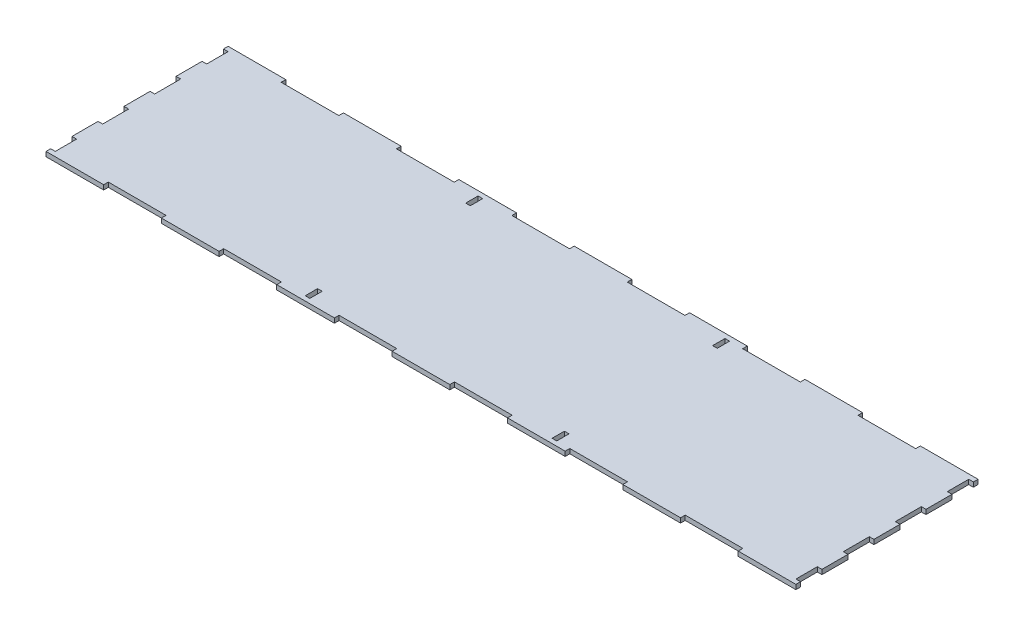
SolidWorks part; units mm, degrees
ref_plane "Front Plane" through (0, 0, 0) normal (0, 0, 1) x (1, 0, 0)
ref_plane "Top Plane" through (0, 0, 0) normal (0, 1, 0) x (1, 0, 0)
ref_plane "Right Plane" through (0, 0, 0) normal (1, 0, 0) x (0, 0, -1)
sketch "Sketch1" plane through (0, 0, 0) normal (0, 1, 0) x (1, 0, 0)
  line L0 (0, 88.9) -> (0, -88.9) construction
  line L1 (-381, 88.9) -> (381, 88.9)
  line L2 (-381, 88.9) -> (-381, -88.9)
  line L3 (-381, -88.9) -> (381, -88.9)
  line L4 (381, 88.9) -> (381, -88.9)
  line L5 (-381, 40.1411) -> (-381, 66.9018)
  line L6 (-381, 66.9018) -> (-385.7625, 66.9018)
  line L7 (-381, 66.9018) -> (-381, 93.6625)
  line L8 (-381, 93.6625) -> (-385.7625, 93.6625)
  line L9 (-385.7625, 66.9018) -> (-385.7625, 93.6625)
  line L14 (-326.4144, -88.9) -> (-385.7625, -88.9)
  line L15 (-326.4144, -88.9) -> (-326.4144, -93.6625)
  line L16 (-326.4144, -93.6625) -> (-385.7625, -93.6625)
  line L17 (-385.7625, -88.9) -> (-385.7625, -93.6625)
  line L18 (381, 66.9018) -> (385.7625, 66.9018)
  line L19 (381, 66.9018) -> (381, 93.6625)
  line L20 (381, 93.6625) -> (385.7625, 93.6625)
  line L21 (385.7625, 66.9018) -> (385.7625, 93.6625)
  line L22 (-326.4144, 88.9) -> (-385.7625, 88.9)
  line L23 (-326.4144, 88.9) -> (-326.4144, 93.6625)
  line L24 (-326.4144, 93.6625) -> (-385.7625, 93.6625)
  line L25 (-385.7625, 88.9) -> (-385.7625, 93.6625)
  line L26 (-381, 40.1411) -> (-385.7625, 40.1411)
  line L27 (-385.7625, 40.1411) -> (-385.7625, 66.9018)
  line L28 (-381, 66.9018) -> (-385.7625, 66.9018)
  line L29 (381, 40.1411) -> (381, 66.9018)
  line L30 (381, 40.1411) -> (385.7625, 40.1411)
  line L31 (385.7625, 40.1411) -> (385.7625, 66.9018)
  line L32 (381, 66.9018) -> (385.7625, 66.9018)
  line L33 (-381, 13.3804) -> (-381, 40.1411)
  line L34 (-381, 13.3804) -> (-385.7625, 13.3804)
  line L35 (-385.7625, 13.3804) -> (-385.7625, 40.1411)
  line L36 (-381, 40.1411) -> (-385.7625, 40.1411)
  line L37 (381, 13.3804) -> (381, 40.1411)
  line L38 (381, 13.3804) -> (385.7625, 13.3804)
  line L39 (385.7625, 13.3804) -> (385.7625, 40.1411)
  line L40 (381, 40.1411) -> (385.7625, 40.1411)
  line L41 (-381, -13.3804) -> (-381, 13.3804)
  line L42 (-381, -13.3804) -> (-385.7625, -13.3804)
  line L43 (-385.7625, -13.3804) -> (-385.7625, 13.3804)
  line L44 (-381, 13.3804) -> (-385.7625, 13.3804)
  line L45 (381, -13.3804) -> (381, 13.3804)
  line L46 (381, -13.3804) -> (385.7625, -13.3804)
  line L47 (385.7625, -13.3804) -> (385.7625, 13.3804)
  line L48 (381, 13.3804) -> (385.7625, 13.3804)
  line L49 (-381, -40.1411) -> (-381, -13.3804)
  line L50 (-381, -40.1411) -> (-385.7625, -40.1411)
  line L51 (-385.7625, -40.1411) -> (-385.7625, -13.3804)
  line L52 (-381, -13.3804) -> (-385.7625, -13.3804)
  line L53 (381, -40.1411) -> (381, -13.3804)
  line L54 (381, -40.1411) -> (385.7625, -40.1411)
  line L55 (385.7625, -40.1411) -> (385.7625, -13.3804)
  line L56 (381, -13.3804) -> (385.7625, -13.3804)
  line L57 (-381, -66.9018) -> (-381, -40.1411)
  line L58 (-381, -66.9018) -> (-385.7625, -66.9018)
  line L59 (-385.7625, -66.9018) -> (-385.7625, -40.1411)
  line L60 (-381, -40.1411) -> (-385.7625, -40.1411)
  line L61 (381, -66.9018) -> (381, -40.1411)
  line L62 (381, -66.9018) -> (385.7625, -66.9018)
  line L63 (385.7625, -66.9018) -> (385.7625, -40.1411)
  line L64 (381, -40.1411) -> (385.7625, -40.1411)
  line L65 (-381, -93.6625) -> (-381, -66.9018)
  line L66 (-381, -93.6625) -> (-385.7625, -93.6625)
  line L67 (-385.7625, -93.6625) -> (-385.7625, -66.9018)
  line L68 (-381, -66.9018) -> (-385.7625, -66.9018)
  line L69 (381, -93.6625) -> (381, -66.9018)
  line L70 (381, -93.6625) -> (385.7625, -93.6625)
  line L71 (385.7625, -93.6625) -> (385.7625, -66.9018)
  line L72 (381, -66.9018) -> (385.7625, -66.9018)
  line L73 (-267.0663, -88.9) -> (-267.0663, -93.6625)
  line L74 (-267.0663, -88.9) -> (-326.4144, -88.9)
  line L75 (-326.4144, -88.9) -> (-326.4144, -93.6625)
  line L76 (-267.0663, -93.6625) -> (-326.4144, -93.6625)
  line L77 (-267.0663, 88.9) -> (-267.0663, 93.6625)
  line L78 (-267.0663, 88.9) -> (-326.4144, 88.9)
  line L79 (-326.4144, 88.9) -> (-326.4144, 93.6625)
  line L80 (-267.0663, 93.6625) -> (-326.4144, 93.6625)
  line L81 (-207.7183, -88.9) -> (-207.7183, -93.6625)
  line L82 (-207.7183, -88.9) -> (-267.0663, -88.9)
  line L83 (-267.0663, -88.9) -> (-267.0663, -93.6625)
  line L84 (-207.7183, -93.6625) -> (-267.0663, -93.6625)
  line L85 (-207.7183, 88.9) -> (-207.7183, 93.6625)
  line L86 (-207.7183, 88.9) -> (-267.0663, 88.9)
  line L87 (-267.0663, 88.9) -> (-267.0663, 93.6625)
  line L88 (-207.7183, 93.6625) -> (-267.0663, 93.6625)
  line L89 (-148.3702, -88.9) -> (-148.3702, -93.6625)
  line L90 (-148.3702, -88.9) -> (-207.7183, -88.9)
  line L91 (-207.7183, -88.9) -> (-207.7183, -93.6625)
  line L92 (-148.3702, -93.6625) -> (-207.7183, -93.6625)
  line L93 (-148.3702, 88.9) -> (-148.3702, 93.6625)
  line L94 (-148.3702, 88.9) -> (-207.7183, 88.9)
  line L95 (-207.7183, 88.9) -> (-207.7183, 93.6625)
  line L96 (-148.3702, 93.6625) -> (-207.7183, 93.6625)
  line L97 (-89.0221, -88.9) -> (-89.0221, -93.6625)
  line L98 (-89.0221, -88.9) -> (-148.3702, -88.9)
  line L99 (-148.3702, -88.9) -> (-148.3702, -93.6625)
  line L100 (-89.0221, -93.6625) -> (-148.3702, -93.6625)
  line L101 (-89.0221, 88.9) -> (-89.0221, 93.6625)
  line L102 (-89.0221, 88.9) -> (-148.3702, 88.9)
  line L103 (-148.3702, 88.9) -> (-148.3702, 93.6625)
  line L104 (-89.0221, 93.6625) -> (-148.3702, 93.6625)
  line L105 (-29.674, -88.9) -> (-29.674, -93.6625)
  line L106 (-29.674, -88.9) -> (-89.0221, -88.9)
  line L107 (-89.0221, -88.9) -> (-89.0221, -93.6625)
  line L108 (-29.674, -93.6625) -> (-89.0221, -93.6625)
  line L109 (-29.674, 88.9) -> (-29.674, 93.6625)
  line L110 (-29.674, 88.9) -> (-89.0221, 88.9)
  line L111 (-89.0221, 88.9) -> (-89.0221, 93.6625)
  line L112 (-29.674, 93.6625) -> (-89.0221, 93.6625)
  line L113 (29.674, -88.9) -> (29.674, -93.6625)
  line L114 (29.674, -88.9) -> (-29.674, -88.9)
  line L115 (-29.674, -88.9) -> (-29.674, -93.6625)
  line L116 (29.674, -93.6625) -> (-29.674, -93.6625)
  line L117 (29.674, 88.9) -> (29.674, 93.6625)
  line L118 (29.674, 88.9) -> (-29.674, 88.9)
  line L119 (-29.674, 88.9) -> (-29.674, 93.6625)
  line L120 (29.674, 93.6625) -> (-29.674, 93.6625)
  line L121 (89.0221, -88.9) -> (89.0221, -93.6625)
  line L122 (89.0221, -88.9) -> (29.674, -88.9)
  line L123 (29.674, -88.9) -> (29.674, -93.6625)
  line L124 (89.0221, -93.6625) -> (29.674, -93.6625)
  line L125 (89.0221, 88.9) -> (89.0221, 93.6625)
  line L126 (89.0221, 88.9) -> (29.674, 88.9)
  line L127 (29.674, 88.9) -> (29.674, 93.6625)
  line L128 (89.0221, 93.6625) -> (29.674, 93.6625)
  line L129 (148.3702, -88.9) -> (148.3702, -93.6625)
  line L130 (148.3702, -88.9) -> (89.0221, -88.9)
  line L131 (89.0221, -88.9) -> (89.0221, -93.6625)
  line L132 (148.3702, -93.6625) -> (89.0221, -93.6625)
  line L133 (148.3702, 88.9) -> (148.3702, 93.6625)
  line L134 (148.3702, 88.9) -> (89.0221, 88.9)
  line L135 (89.0221, 88.9) -> (89.0221, 93.6625)
  line L136 (148.3702, 93.6625) -> (89.0221, 93.6625)
  line L137 (207.7183, -88.9) -> (207.7183, -93.6625)
  line L138 (207.7183, -88.9) -> (148.3702, -88.9)
  line L139 (148.3702, -88.9) -> (148.3702, -93.6625)
  line L140 (207.7183, -93.6625) -> (148.3702, -93.6625)
  line L141 (207.7183, 88.9) -> (207.7183, 93.6625)
  line L142 (207.7183, 88.9) -> (148.3702, 88.9)
  line L143 (148.3702, 88.9) -> (148.3702, 93.6625)
  line L144 (207.7183, 93.6625) -> (148.3702, 93.6625)
  line L145 (267.0663, -88.9) -> (267.0663, -93.6625)
  line L146 (267.0663, -88.9) -> (207.7183, -88.9)
  line L147 (207.7183, -88.9) -> (207.7183, -93.6625)
  line L148 (267.0663, -93.6625) -> (207.7183, -93.6625)
  line L149 (267.0663, 88.9) -> (267.0663, 93.6625)
  line L150 (267.0663, 88.9) -> (207.7183, 88.9)
  line L151 (207.7183, 88.9) -> (207.7183, 93.6625)
  line L152 (267.0663, 93.6625) -> (207.7183, 93.6625)
  line L185 (326.4144, -88.9) -> (326.4144, -93.6625)
  line L186 (326.4144, -88.9) -> (267.0663, -88.9)
  line L187 (267.0663, -88.9) -> (267.0663, -93.6625)
  line L188 (326.4144, -93.6625) -> (267.0663, -93.6625)
  line L189 (326.4144, 88.9) -> (326.4144, 93.6625)
  line L190 (326.4144, 88.9) -> (267.0663, 88.9)
  line L191 (267.0663, 88.9) -> (267.0663, 93.6625)
  line L192 (326.4144, 93.6625) -> (267.0663, 93.6625)
  line L193 (385.7625, -88.9) -> (385.7625, -93.6625)
  line L194 (385.7625, -88.9) -> (326.4144, -88.9)
  line L195 (326.4144, -88.9) -> (326.4144, -93.6625)
  line L196 (385.7625, -93.6625) -> (326.4144, -93.6625)
  line L197 (385.7625, 88.9) -> (385.7625, 93.6625)
  line L198 (385.7625, 88.9) -> (326.4144, 88.9)
  line L199 (326.4144, 88.9) -> (326.4144, 93.6625)
  line L200 (385.7625, 93.6625) -> (326.4144, 93.6625)
  point P8 (0, 88.9)
  point P9 (0, 0)
  dimension "D1" = 762
  dimension "D2" = 177.8
  dimension "D3" = 187.325
  dimension "D5" = 771.525
  dimension "D6" = 26.7607
  dimension "D8" = 59.3481
  dimension "D4" = 7
  dimension "D7" = 13
extrude "Boss-Extrude1" add sketch "Sketch1" along normal blind 4.7625
sketch "Sketch2" plane through (0, 4.7625, 0) normal (0, 1, 0) x (1, 0, 0)
  line L0 (-124.6188, 0) -> (124.6188, 0) construction
  line L1 (-129.3812, 15.4404) -> (-124.6188, 15.4404) construction
  line L2 (-129.3812, 15.4404) -> (-129.3812, -15.4404) construction
  line L3 (-129.3812, -15.4404) -> (-124.6188, -15.4404) construction
  line L4 (-124.6188, 15.4404) -> (-124.6188, -15.4404) construction
  line L5 (124.6188, 14.3164) -> (129.3812, 14.3164) construction
  line L6 (124.6188, 14.3164) -> (124.6188, -14.3164) construction
  line L7 (124.6188, -14.3164) -> (129.3812, -14.3164) construction
  line L8 (129.3812, 14.3164) -> (129.3812, -14.3164) construction
  line L9 (-130.175, 24.6215) -> (-123.825, 24.6215) construction
  line L10 (-127, 24.6215) -> (-127, 15.4404) construction
  line L12 (-123.825, 76.2) -> (-119.0625, 76.2)
  line L13 (-123.825, 76.2) -> (-123.825, 88.9)
  line L14 (-123.825, 88.9) -> (-119.0625, 88.9)
  line L15 (-119.0625, 76.2) -> (-119.0625, 88.9)
  line L16 (-123.825, 24.6215) -> (-123.825, 76.2) construction
  line L18 (-119.0625, -88.9) -> (-123.825, -88.9)
  line L19 (-119.0625, -88.9) -> (-119.0625, -76.2)
  line L20 (-119.0625, -76.2) -> (-123.825, -76.2)
  line L21 (-123.825, -88.9) -> (-123.825, -76.2)
  line L31 (-207.7183, 88.9) -> (-148.3702, 88.9) construction
  line L32 (-207.7183, -88.9) -> (-148.3702, -88.9) construction
  line L33 (130.175, 76.2) -> (130.175, 88.9)
  line L34 (130.175, 76.2) -> (134.9375, 76.2)
  line L35 (134.9375, 76.2) -> (134.9375, 88.9)
  line L36 (130.175, 88.9) -> (134.9375, 88.9)
  line L37 (134.9375, -88.9) -> (134.9375, -76.2)
  line L38 (134.9375, -88.9) -> (130.175, -88.9)
  line L39 (130.175, -88.9) -> (130.175, -76.2)
  line L40 (134.9375, -76.2) -> (130.175, -76.2)
  line L41 (123.825, 24.6215) -> (130.175, 24.6215) construction
  line L42 (127, 24.6215) -> (127, 14.3164) construction
  line L43 (130.175, 24.6215) -> (130.175, 76.2) construction
  point P10 (0, 0)
  point P43 (127, 14.3164)
  dimension "D1" = 4.7625
  dimension "D2" = 6.35
  dimension "D4" = 4.7625
  dimension "D5" = 12.7
  dimension "D3" = 254
  dimension "D6" = 2
extrude "Cut-Extrude1" cut sketch "Sketch2" against normal through all
equation "\"Height\"= 12in"
equation "\"Depth\"= 7in"
equation "\"WallThickness\"= 0.1875in"
equation "\"FloorThickness\"= 0.1875in"
equation "\"D1@Sketch1\"=\"Width\""
equation "\"D2@Sketch1\"=\"Depth\""
equation "\"D3@Sketch1\"=\"D2@Sketch1\"+2*\"WallThickness\""
equation "\"D5@Sketch1\"=\"D1@Sketch1\"+2*\"WallThickness\""
equation "\"D6@Sketch1\"=\"D3@Sketch1\"/\"D4@Sketch1\""
equation "\"D8@Sketch1\"=\"D5@Sketch1\"/\"D7@Sketch1\""
equation "\"D1@Boss-Extrude1\"=\"FloorThickness\""
equation "\"D1@Sketch2\"=\"WallThickness\""
equation "\"D2@Sketch2\"=\"WallThickness\"+(1/16in)"
equation "\"D4@Sketch2\"=\"WallThickness\""
equation "\"Width\" = 30in"
